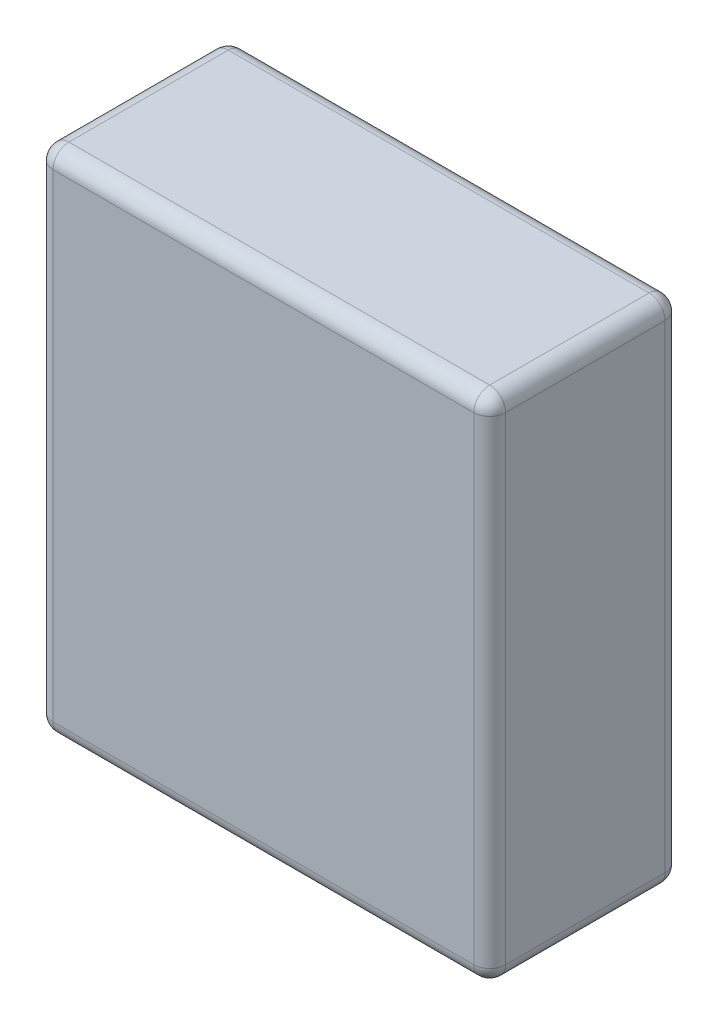
SolidWorks part; units mm, degrees
ref_plane "Front Plane" through (0, 0, 0) normal (0, 0, 1) x (1, 0, 0)
ref_plane "Top Plane" through (0, 0, 0) normal (0, 1, 0) x (1, 0, 0)
ref_plane "Right Plane" through (0, 0, 0) normal (1, 0, 0) x (0, 0, -1)
sketch "Sketch1" plane through (0, 0, 0) normal (0, 1, 0) x (1, 0, 0)
  line L1 (71, 30) -> (-71, 30)
  line L2 (71, 30) -> (71, -30)
  line L3 (71, -30) -> (-71, -30)
  line L4 (-71, 30) -> (-71, -30)
  line L5 (71, 30) -> (-71, -30) construction
  line L6 (71, -30) -> (-71, 30) construction
  point P0 (0, 0)
  dimension "D1" = 142
  dimension "D2" = 60
extrude "Boss-Extrude1" add sketch "Sketch1" along normal blind 160
fillet "Fillet1" radius 5 12 edges at (-71, 0, 0) (-71, 80, -30) (0, 0, -30) (71, 80, -30) (71, 0, 0) (-71, 80, 30) (71, 80, 30) (0, 0, 30) (0, 160, -30) (71, 160, 0) (0, 160, 30) (-71, 160, 0)
